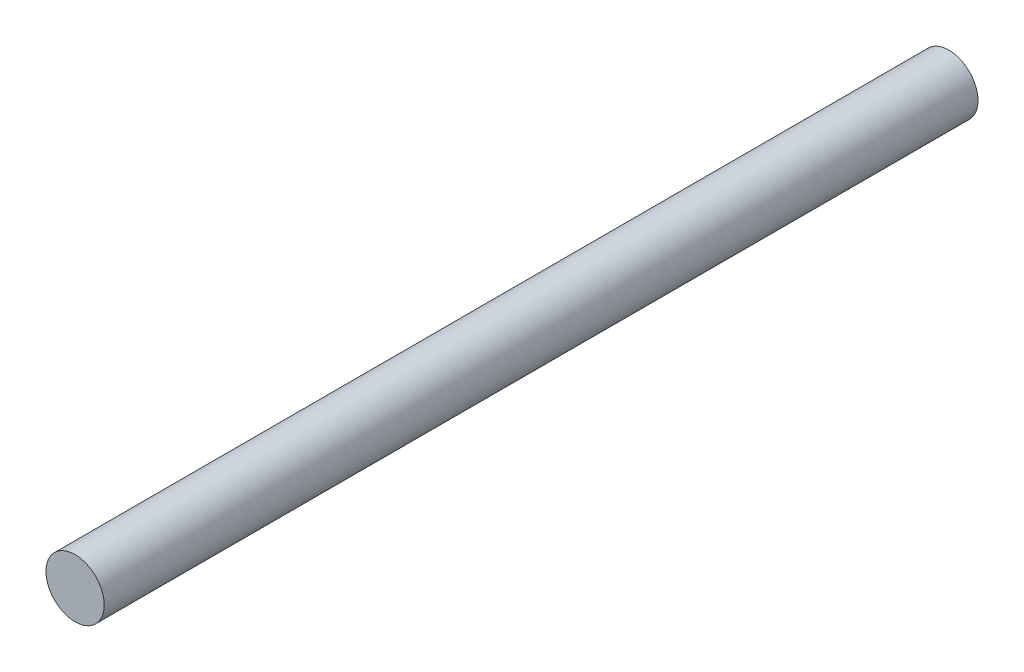
SolidWorks part; units mm, degrees
ref_plane "前视基准面" through (0, 0, 0) normal (0, 0, 1) x (1, 0, 0)
ref_plane "上视基准面" through (0, 0, 0) normal (0, 1, 0) x (1, 0, 0)
ref_plane "右视基准面" through (0, 0, 0) normal (1, 0, 0) x (0, 0, -1)
other "Configuration Table"
sketch "草图1" plane through (0, 0, 0) normal (0, 0, 1) x (1, 0, 0)
  circle A0 centre (0, 0) radius 5
extrude "M10_threaded_spindle_150" add sketch "草图1" along normal blind 150
